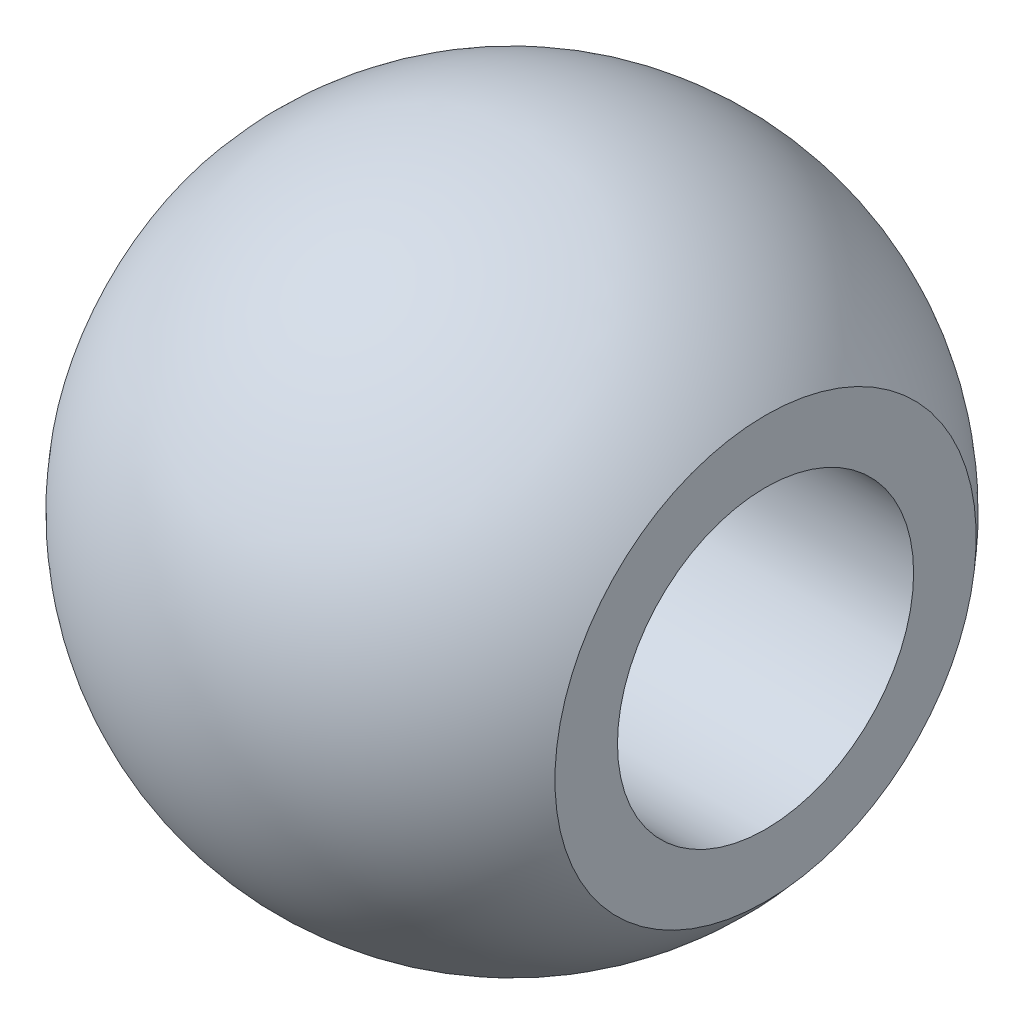
SolidWorks part; units mm, degrees
ref_plane "Piano frontale" through (0, 0, 0) normal (0, 0, 1) x (1, 0, 0)
ref_plane "Piano superiore" through (0, 0, 0) normal (0, 1, 0) x (1, 0, 0)
ref_plane "Piano destro" through (0, 0, 0) normal (1, 0, 0) x (0, 0, -1)
sketch "Schizzo1" plane through (0, 0, 0) normal (0, 0, 1) x (1, 0, 0)
  line L0 (0, 3.25) -> (0, -3.25)
  arc A0 (0, -3.25) -> (0, 3.25) centre (0, 0) ccw
  dimension "D1" = 6.5
revolve "Rivoluzione1" add sketch "Schizzo1" angle 360 about L0
sketch "Schizzo2" plane through (0, 0, 0) normal (1, 0, 0) x (0, 0, -1)
  circle A0 centre (0, 0) radius 1.46
  dimension "D1" = 2.92
extrude "Taglio-Estrusione1" cut sketch "Schizzo2" against normal through all and the other way through all
sketch "Schizzo3" plane through (0, 0, 0) normal (0, 0, 1) x (1, 0, 0)
  line L0 (0, 0) -> (0, -5.7234) construction
  line L1 (2.5, 4.4051) -> (2.5, -5.3697)
  line L2 (-2.5, -5.3697) -> (-2.5, 4.5337)
  line L3 (-2.9036, 3.2514) -> (2.9036, 3.2514)
  line L4 (2.9036, 3.2514) -> (2.9036, -3.25)
  line L5 (2.9036, -3.25) -> (-2.9036, -3.25)
  line L6 (-2.9036, -3.25) -> (-2.9036, 3.2514)
  line L7 (-2.9036, 1.46) -> (-2.9036, -1.46) construction
  line L8 (2.9036, 1.46) -> (2.9036, -1.46) construction
  arc A0 (-2.9036, -1.46) -> (2.9036, -1.46) centre (0, 0) ccw construction
  dimension "D1" = 5
extrude "Taglio-Estrusione2" cut sketch "Schizzo3" against normal through all and the other way through all contours L5 L4 L3 L1 | L6 L5 L2 L3
